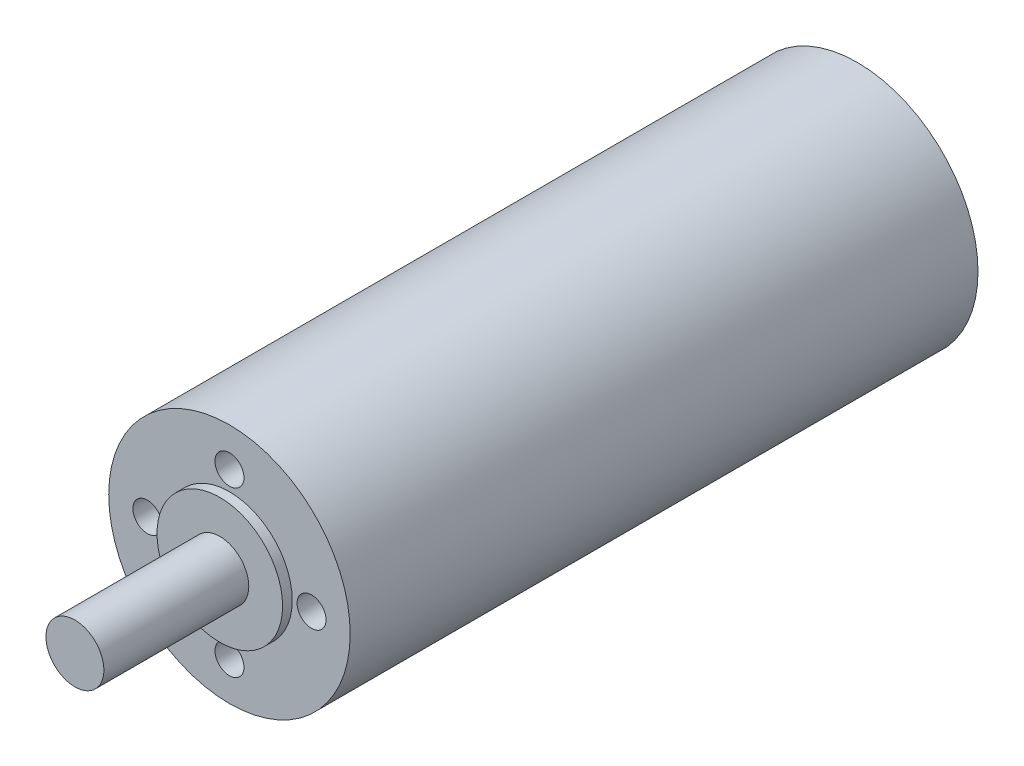
SolidWorks part; units mm, degrees
ref_plane "Plano frontal" through (0, 0, 0) normal (0, 0, 1) x (1, 0, 0)
ref_plane "Plano superior" through (0, 0, 0) normal (0, 1, 0) x (1, 0, 0)
ref_plane "Plano direito" through (0, 0, 0) normal (1, 0, 0) x (0, 0, -1)
sketch "Esboço1" plane through (0, 0, 0) normal (0, 0, 1) x (1, 0, 0)
  circle A0 centre (0, 0) radius 12.5
  dimension "D1" = 25
extrude "Ressalto-extrusão1" add sketch "Esboço1" along normal blind 65
sketch "Esboço2" plane through (0, 0, 65) normal (0, 0, 1) x (1, 0, 0)
  circle A0 centre (0, 0) radius 6.5
  dimension "D1" = 13
extrude "Ressalto-extrusão2" add sketch "Esboço2" along normal blind 1
sketch "Esboço3" plane through (0, 0, 66) normal (0, 0, 1) x (1, 0, 0)
  circle A0 centre (0, 0) radius 3
  dimension "D1" = 6
extrude "Ressalto-extrusão3" add sketch "Esboço3" along normal blind 15
sketch "Esboço4" plane through (0, 0, 65) normal (0, 0, 1) x (1, 0, 0)
  line L0 (0, -8.5) -> (0, 0) construction
  circle A0 centre (0, -8.5) radius 1.5
  dimension "D1" = 3
  dimension "D2" = 8.5
extrude "Corte-extrusão1" cut sketch "Esboço4" against normal blind 4
pattern_circular "PadrãoCircular1" count 4 over 360 about axis through (0, 0, 0) along (0, 0, 1) of "Corte-extrusão1"
